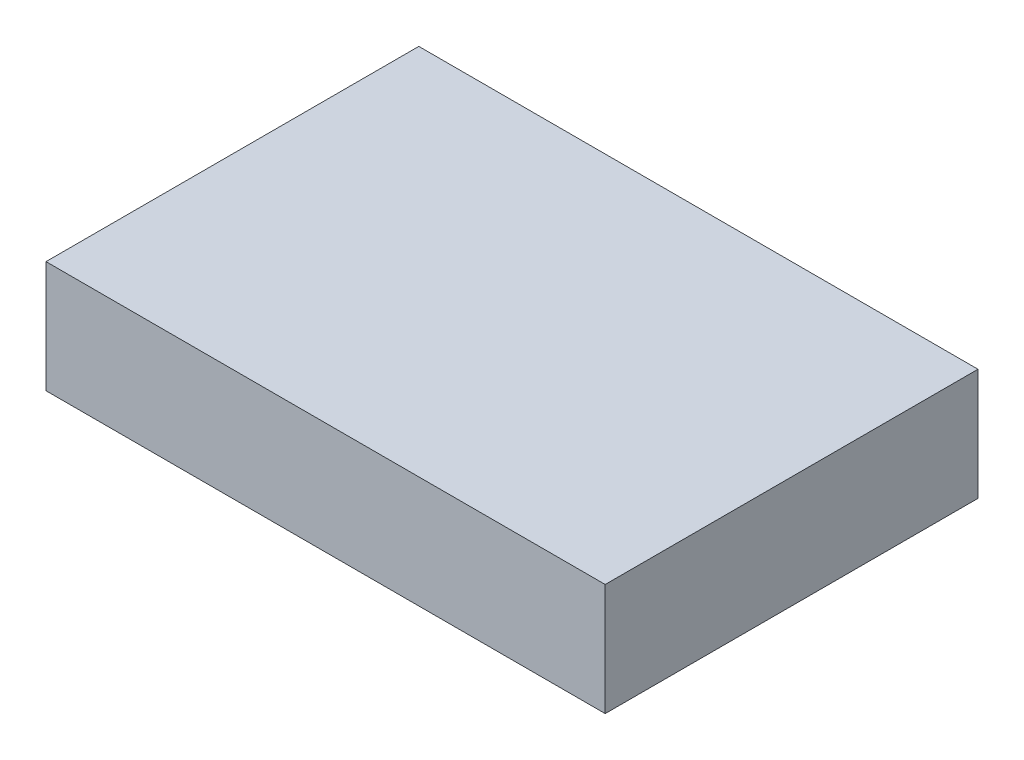
SolidWorks part; units mm, degrees
ref_plane "Front Plane" through (0, 0, 0) normal (0, 0, 1) x (1, 0, 0)
ref_plane "Top Plane" through (0, 0, 0) normal (0, 1, 0) x (1, 0, 0)
ref_plane "Right Plane" through (0, 0, 0) normal (1, 0, 0) x (0, 0, -1)
other "Configuration Table"
sketch "Sketch1" plane through (0, 0, 0) normal (0, 0, 1) x (1, 0, 0)
  line L1 (0, 0) -> (150, 0)
  line L2 (0, 0) -> (0, 30)
  line L3 (0, 30) -> (150, 30)
  line L4 (150, 0) -> (150, 30)
  dimension "D1" = 150
  dimension "D2" = 30
extrude "Extrude1" add sketch "Sketch1" along normal blind 100
